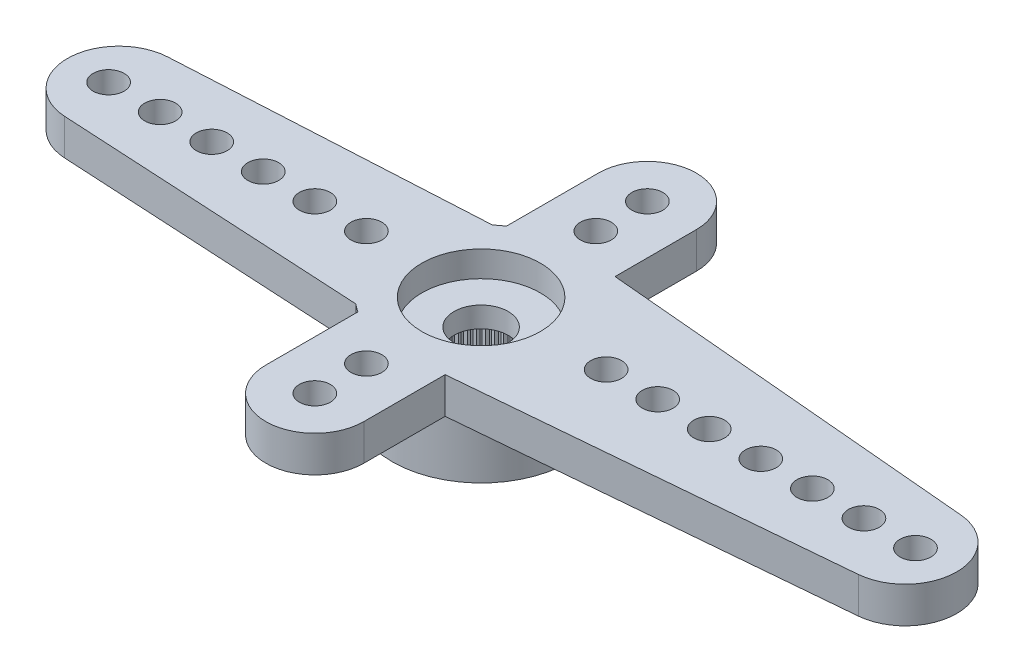
SolidWorks part; units mm, degrees
material "PVC Rígido"
ref_plane "Plano frontal" through (0, 0, 0) normal (0, 0, 1) x (1, 0, 0)
ref_plane "Plano superior" through (0, 0, 0) normal (0, 1, 0) x (1, 0, 0)
ref_plane "Plano direito" through (0, 0, 0) normal (1, 0, 0) x (0, 0, -1)
sketch "Esboço1" plane through (0, 0, 0) normal (0, 1, 0) x (1, 0, 0)
  line L0 (0, 0) -> (-14.05, 0) construction
  line L1 (-14.1591, 1.997) -> (-2.2091, 2.65)
  line L2 (-2.2091, -2.65) -> (-14.1591, -1.997)
  arc A0 (-2.2091, -2.65) -> (-2.2091, 2.65) centre (0, 0) ccw
  arc A1 (-14.1591, 1.997) -> (-14.1591, -1.997) centre (-14.05, 0) ccw
  dimension "D1" = 6.9
  dimension "D2" = 4
  dimension "D3" = 19.5
  dimension "D4" = 5.3
extrude "Ressalto-extrusão1" add sketch "Esboço1" against normal blind 1.4
sketch "Esboço2" plane through (0, -1.4, 0) normal (0, -1, 0) x (1, 0, 0)
  arc A0 (-2.2091, -2.65) -> (-2.2091, 2.65) centre (0, 0) ccw construction
  circle A1 centre (0, 0) radius 3.45
extrude "Ressalto-extrusão2" add sketch "Esboço2" along normal offset from surface (2.4 mm away) 3.8 up to face at (-7.242, 0, 0)
hole_wizard "Furo1" positions "Esboço9" profile "Esboço10" legacy end condition through all
sketch "Esboço9" plane through (0, 0, 0) normal (0, 1, 0) x (1, 0, 0)
  line L1 (-14.45, 0) -> (0, 0) construction
  arc A2 (-14.1591, 1.997) -> (-14.1591, -1.997) centre (-14.05, 0) ccw construction
  point P0 (-14.45, 0)
  point P19 (-16.05, 0)
  dimension "D1" = 1.6
sketch "Esboço10" plane through (-14.45, 0, 0) normal (1, 0, 0) x (0, 0, 1)
  line L0 (0, 0) -> (0, 3.8)
  line L1 (0, 3.8) -> (0.6, 3.8)
  line L2 (0.6, 3.8) -> (0.6, 0)
  line L3 (0.6, 0) -> (0, 0)
  line L4 (0, 110) -> (0, -10) construction
  dimension "Diameter" = 1.2
  dimension "Depth" = 3.8
pattern_linear "Padrão linear1" count 6 spacing 2 along (1, 0, 0) of "Furo1"
sketch "Esboço12" plane through (0, 0, 0) normal (0, 1, 0) x (1, 0, 0)
  line L0 (0.3041, 3.4366) -> (16.6263, 1.9922)
  line L1 (16.6263, -1.9922) -> (0.3041, -3.4366)
  arc A0 (-2.2091, -2.65) -> (-2.2091, 2.65) centre (0, 0) ccw construction
  arc A1 (0.3041, -3.4366) -> (0.3041, 3.4366) centre (0, 0) ccw
  arc A2 (16.6263, 1.9922) -> (16.6263, -1.9922) centre (16.45, 0) cw
  arc A3 (-14.1591, 1.997) -> (-14.1591, -1.997) centre (-14.05, 0) ccw construction
  dimension "D1" = 2
  dimension "D2" = 34.5
extrude "Ressalto-extrusão3" add sketch "Esboço12" against normal up to surface (1.4 mm away) up to face at (-12.45, -1.4, 0.6)
hole_wizard "Furo2" positions "Esboço13" profile "Esboço14" legacy end condition through all
sketch "Esboço13" plane through (0, 0, 0) normal (0, 1, 0) x (1, 0, 0)
  line L0 (0, 0) -> (16.85, 0) construction
  arc A0 (16.6263, -1.9922) -> (16.6263, 1.9922) centre (16.45, 0) ccw construction
  point P0 (16.85, 0)
  point P6 (18.45, 0)
  dimension "D1" = 1.6
sketch "Esboço14" plane through (16.85, 0, 0) normal (1, 0, 0) x (0, 0, 1)
  line L0 (0, 0) -> (0, 3.8)
  line L1 (0, 3.8) -> (0.6, 3.8)
  line L2 (0.6, 3.8) -> (0.6, 0)
  line L3 (0.6, 0) -> (0, 0)
  line L4 (0, 110) -> (0, -10) construction
  dimension "Diameter" = 1.2
  dimension "Depth" = 3.8
pattern_linear "Padrão linear2" count 7 spacing 2 along (-1, 0, 0) of "Furo2"
sketch "Esboço16" plane through (0, 0, 0) normal (0, 1, 0) x (1, 0, 0)
  line L0 (0, -6.45) -> (0, 6.45) construction
  line L1 (-1.9, -6.45) -> (-1.9, 6.45)
  line L2 (1.9, -6.45) -> (1.9, 6.45)
  arc A0 (-1.9, -6.45) -> (1.9, -6.45) centre (0, -6.45) ccw
  arc A1 (1.9, 6.45) -> (-1.9, 6.45) centre (0, 6.45) ccw
  point P2 (0, 0)
  dimension "D2" = 16.7
  dimension "D1" = 3.8
extrude "Ressalto-extrusão4" add sketch "Esboço16" against normal up to surface (1.4 mm away) up to face at (14.85, -1.4, 0.6)
hole_wizard "Furo3" positions "Esboço17" profile "Esboço18" legacy end condition through all
sketch "Esboço17" plane through (0, 0, 0) normal (0, 1, 0) x (1, 0, 0)
  point P0 (0, -6.45)
sketch "Esboço18" plane through (0, 0, 6.45) normal (1, 0, 0) x (0, 0, 1)
  line L0 (0, 0) -> (0, 3.8)
  line L1 (0, 3.8) -> (0.6, 3.8)
  line L2 (0.6, 3.8) -> (0.6, 0)
  line L3 (0.6, 0) -> (0, 0)
  line L4 (0, 110) -> (0, -10) construction
  dimension "Diameter" = 1.2
  dimension "Depth" = 3.8
pattern_linear "Padrão linear3" count 2 spacing 2 along (0, 0, -1) of "Furo3"
pattern_circular "PadrãoCircular1" count 2 over 360 about axis through (0, 0, 0) along (0, 1, 0) of "Padrão linear3", "Furo3"
hole_wizard "Furo4" positions "Esboço3" profile "Esboço4" legacy
sketch "Esboço3" plane through (0, -3.8, 0) normal (0, -1, 0) x (-1, 0, 0)
  point P0 (0, 0)
sketch "Esboço4" plane through (0, -3.8, 0) normal (1, 0, 0) x (0, 0, -1)
  line L0 (0, 0) -> (0, 2)
  line L1 (0, 2) -> (2.475, 2)
  line L2 (2.475, 2) -> (2.475, 0)
  line L3 (2.475, 0) -> (0, 0)
  line L4 (0, 110) -> (0, -10) construction
  dimension "Diameter" = 4.95
  dimension "Depth" = 2
hole_wizard "Furo5" positions "Esboço5" profile "Esboço6" legacy
sketch "Esboço5" plane through (0, 0, 0) normal (0, 1, 0) x (1, 0, 0)
  point P0 (0, 0)
sketch "Esboço6" plane through (0, 0, 0) normal (1, 0, 0) x (0, 0, 1)
  line L0 (0, 0) -> (0, 1)
  line L1 (0, 1) -> (2.3, 1)
  line L2 (2.3, 1) -> (2.3, 0)
  line L3 (2.3, 0) -> (0, 0)
  line L4 (0, 110) -> (0, -10) construction
  dimension "Diameter" = 4.6
  dimension "Depth" = 1
hole_wizard "Furo6" positions "Esboço7" profile "Esboço8" legacy end condition through all
sketch "Esboço7" plane through (0, 0, 0) normal (0, 1, 0) x (1, 0, 0)
  point P0 (0, 0)
sketch "Esboço8" plane through (0, 0, 0) normal (1, 0, 0) x (0, 0, 1)
  line L0 (0, 0) -> (0, 3.8)
  line L1 (0, 3.8) -> (1.05, 3.8)
  line L2 (1.05, 3.8) -> (1.05, 0)
  line L3 (1.05, 0) -> (0, 0)
  line L4 (0, 110) -> (0, -10) construction
  dimension "Diameter" = 2.1
  dimension "Depth" = 3.8
sketch "Esboço11" plane through (0, -3.8, 0) normal (0, -1, 0) x (1, 0, 0)
  line L0 (-0.0981, 2.4731) -> (0, 2.375)
  line L1 (0, 2.375) -> (0.0981, 2.4731)
  line L2 (0, 0) -> (0, 2.475) construction
  circle A0 centre (0, 0) radius 2.375 construction
  circle A1 centre (0, 0) radius 2.475
  arc A2 (0.0981, 2.4731) -> (-0.0981, 2.4731) centre (0, 0) ccw
  dimension "D3" = 4.75
  dimension "D2" = 0.1
  dimension "D1" = 0
extrude "Ressalto-extrusão5" add sketch "Esboço11" against normal up to surface (2 mm away) up to face at (0, -1.8, 1.05)
pattern_circular "PadrãoCircular2" count 60 over 360 about axis through (0, 0, 0) along (0, 1, 0) of "Ressalto-extrusão5"
sketch "Sketch1" plane through (0, 0, 0) normal (0, 1, 0) x (1, 0, 0)
  line L8 (-1.9, 6.45) -> (-1.9, 2.8797)
  line L9 (-2.2091, 2.65) -> (-14.1591, 1.997)
  line L10 (-14.1591, -1.997) -> (-2.2091, -2.65)
  line L11 (-1.9, -2.8797) -> (-1.9, -6.45)
  line L12 (1.9, -6.45) -> (1.9, -3.2953)
  line L13 (1.9, -3.2953) -> (16.6263, -1.9922)
  line L14 (16.6263, 1.9922) -> (1.9, 3.2953)
  line L15 (1.9, 3.2953) -> (1.9, 6.45)
  line L16 (-1.9, 6.45) -> (-1.9, 2.8797)
  line L17 (-2.2091, 2.65) -> (-14.1591, 1.997)
  line L18 (-14.1591, -1.997) -> (-2.2091, -2.65)
  line L19 (-1.9, -2.8797) -> (-1.9, -6.45)
  line L20 (1.9, -6.45) -> (1.9, -3.2953)
  line L21 (1.9, -3.2953) -> (16.6263, -1.9922)
  line L22 (16.6263, 1.9922) -> (1.9, 3.2953)
  line L23 (1.9, 3.2953) -> (1.9, 6.45)
  circle A0 centre (-14.45, 0) radius 0.6 construction
  circle A1 centre (-12.45, 0) radius 0.6 construction
  circle A2 centre (-10.45, 0) radius 0.6 construction
  circle A3 centre (-8.45, 0) radius 0.6 construction
  circle A4 centre (-6.45, 0) radius 0.6 construction
  circle A5 centre (-4.45, 0) radius 0.6 construction
  arc A6 (-1.9, 2.8797) -> (-2.2091, 2.65) centre (0, 0) ccw
  arc A7 (-14.1591, 1.997) -> (-14.1591, -1.997) centre (-14.05, 0) ccw
  arc A8 (-2.2091, -2.65) -> (-1.9, -2.8797) centre (0, 0) ccw
  arc A9 (-1.9, -6.45) -> (1.9, -6.45) centre (0, -6.45) ccw
  arc A10 (16.6263, -1.9922) -> (16.6263, 1.9922) centre (16.45, 0) ccw
  arc A11 (1.9, 6.45) -> (-1.9, 6.45) centre (0, 6.45) ccw
  arc A12 (-1.9, 2.8797) -> (-2.2091, 2.65) centre (0, 0) ccw
  arc A13 (-14.1591, 1.997) -> (-14.1591, -1.997) centre (-14.05, 0) ccw
  arc A14 (-2.2091, -2.65) -> (-1.9, -2.8797) centre (0, 0) ccw
  arc A15 (-1.9, -6.45) -> (1.9, -6.45) centre (0, -6.45) ccw
  arc A16 (16.6263, -1.9922) -> (16.6263, 1.9922) centre (16.45, 0) ccw
  arc A17 (1.9, 6.45) -> (-1.9, 6.45) centre (0, 6.45) ccw
  circle A18 centre (0, 6.45) radius 0.6 construction
  circle A19 centre (0, 4.45) radius 0.6 construction
  circle A20 centre (16.85, 0) radius 0.6 construction
  circle A21 centre (14.85, 0) radius 0.6 construction
  circle A22 centre (12.85, 0) radius 0.6 construction
  circle A23 centre (10.85, 0) radius 0.6 construction
  circle A24 centre (8.85, 0) radius 0.6 construction
  circle A25 centre (6.85, 0) radius 0.6 construction
  circle A26 centre (4.85, 0) radius 0.6 construction
  circle A27 centre (0, -6.45) radius 0.6 construction
  circle A28 centre (0, -4.45) radius 0.6 construction
  circle A29 centre (0, 6.45) radius 0.6
  circle A30 centre (0, 4.45) radius 0.6
  circle A31 centre (16.85, 0) radius 0.6
  circle A32 centre (14.85, 0) radius 0.6
  circle A33 centre (12.85, 0) radius 0.6
  circle A34 centre (10.85, 0) radius 0.6
  circle A35 centre (8.85, 0) radius 0.6
  circle A36 centre (6.85, 0) radius 0.6
  circle A37 centre (4.85, 0) radius 0.6
  circle A38 centre (0, -6.45) radius 0.6
  circle A39 centre (0, -4.45) radius 0.6
  circle A40 centre (-4.45, 0) radius 0.6
  circle A41 centre (-6.45, 0) radius 0.6
  circle A42 centre (-8.45, 0) radius 0.6
  circle A43 centre (-10.45, 0) radius 0.6
  circle A44 centre (-12.45, 0) radius 0.6
  circle A45 centre (-14.45, 0) radius 0.6
  dimension "D1" = 0
